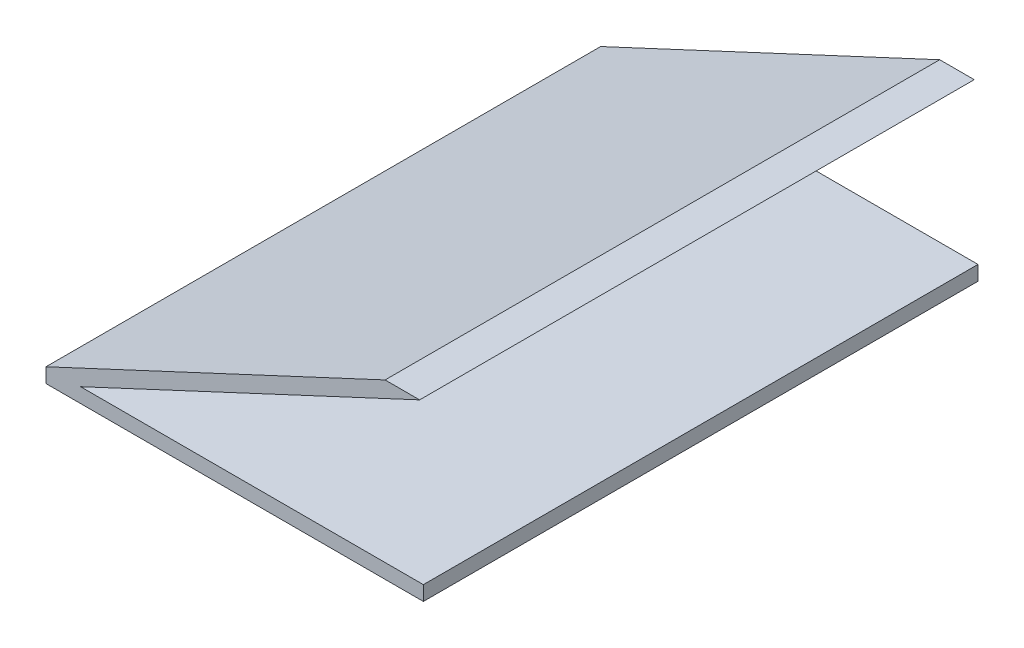
SolidWorks part; units mm, degrees
ref_plane "前视基准面" through (0, 0, 0) normal (0, 0, 1) x (1, 0, 0)
ref_plane "上视基准面" through (0, 0, 0) normal (0, 1, 0) x (1, 0, 0)
ref_plane "右视基准面" through (0, 0, 0) normal (1, 0, 0) x (0, 0, -1)
sketch "草图2" plane through (0, 0, 0) normal (0, 0, 1) x (1, 0, 0)
  line L0 (0, 0) -> (-253.7662, -118.3331)
  line L1 (0, 0) -> (23.662, 0)
  line L2 (23.662, 0) -> (-208.6591, -108.3331)
  line L3 (-208.6591, -108.3331) -> (26.2338, -108.3331)
  line L4 (26.2338, -108.3331) -> (26.2338, -118.3331)
  line L5 (26.2338, -118.3331) -> (-253.7662, -118.3331)
  dimension "D1" = 10
  dimension "D2" = 10
  dimension "D3" = 25
  dimension "D4" = 280
  dimension "D5" = 280
extrude "凸台-拉伸1" add sketch "草图2" along normal blind 380
sketch "草图3" plane through (0, 0, 380) normal (0, 0, 1) x (1, 0, 0)
  line L0 (-232.3211, -108.3331) -> (-253.7662, -118.3331)
  line L1 (0, 0) -> (-253.7662, -118.3331) construction
  line L2 (-253.7662, -118.3331) -> (-232.3211, -118.3331)
  line L3 (-253.7662, -118.3331) -> (26.2338, -118.3331) construction
  line L4 (-232.3211, -118.3331) -> (-232.3211, -108.3331)
  dimension "D1" = 10
extrude "切除-拉伸1" cut sketch "草图3" against normal through all
